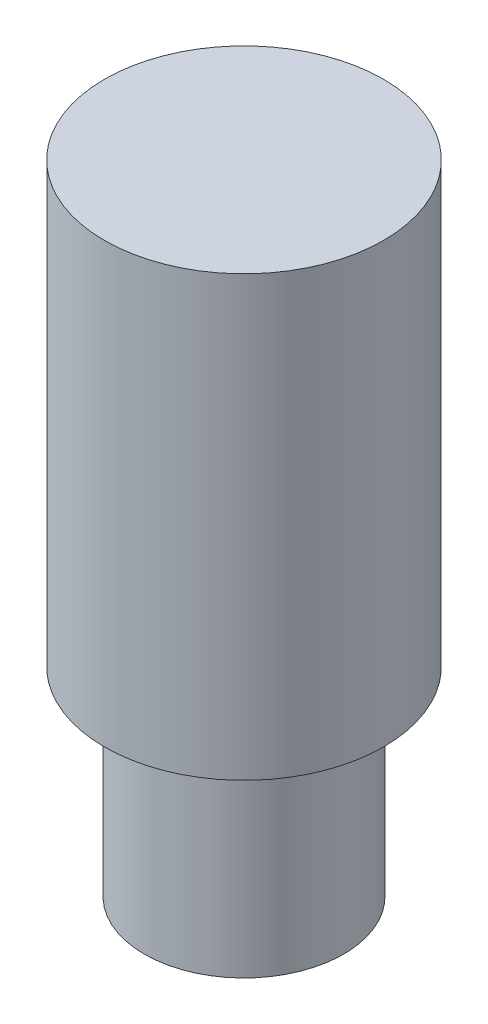
SolidWorks part; units mm, degrees
ref_plane "Front Plane" through (0, 0, 0) normal (0, 0, 1) x (1, 0, 0)
ref_plane "Top Plane" through (0, 0, 0) normal (0, 1, 0) x (1, 0, 0)
ref_plane "Right Plane" through (0, 0, 0) normal (1, 0, 0) x (0, 0, -1)
sketch "Sketch1" plane through (0, 0, 0) normal (0, 1, 0) x (1, 0, 0)
  circle A0 centre (0, 0) radius 2.5
  dimension "D1" = 5
extrude "Boss-Extrude1" add sketch "Sketch1" along normal blind 5
hole_wizard "CSK for M2 Oval Head Machine Screw2" positions "Sketch8" profile "Sketch7" countersink size "M2" standard "ANSI Metric" end condition through all
sketch "Sketch8" plane through (0, 0, 0) normal (0, -1, 0) x (-1, 0, 0)
  point P0 (0, 0)
sketch "Sketch7" plane through (0, 0, 0) normal (1, 0, 0) x (0, 0, -1)
  line L0 (0, 0) -> (0, 5)
  line L1 (0, 5) -> (1.225, 5)
  line L2 (1.2, 4.975) -> (1.2, 1)
  line L3 (1.2, 1) -> (2.2, 0)
  line L5 (2.2, 0) -> (0, 0)
  line L6 (-1.2, 1) -> (-2.2, 0) construction
  line L7 (1.225, 5) -> (1.2, 4.975)
  line L8 (-1.225, 5) -> (-1.2, 4.975) construction
  line L11 (0, -6.35) -> (0, 107.95) construction
  dimension "Thru Hole Dia." = 2.4
  dimension "Thru Hole Depth" = 5
  dimension "Near C'Sink Dia." = 4.4
  dimension "Near C'Sink Angle" = 90
  dimension "Far C'Sink Dia." = 2.45
  dimension "Far C'Sink Angle" = 90
sketch "Sketch2" plane through (0, 5, 0) normal (0, 1, 0) x (1, 0, 0)
  circle A0 centre (0, 0) radius 3.5
  dimension "D1" = 7
extrude "Boss-Extrude2" add sketch "Sketch2" along normal blind 11
sketch "Sketch9" plane through (0, 0, 0) normal (1, 0, 0) x (0, 0, -1)
  line L0 (0, -0.7753) -> (0, 15.9558) construction
  line L1 (0, 15.9558) -> (0, 19.8822) construction
